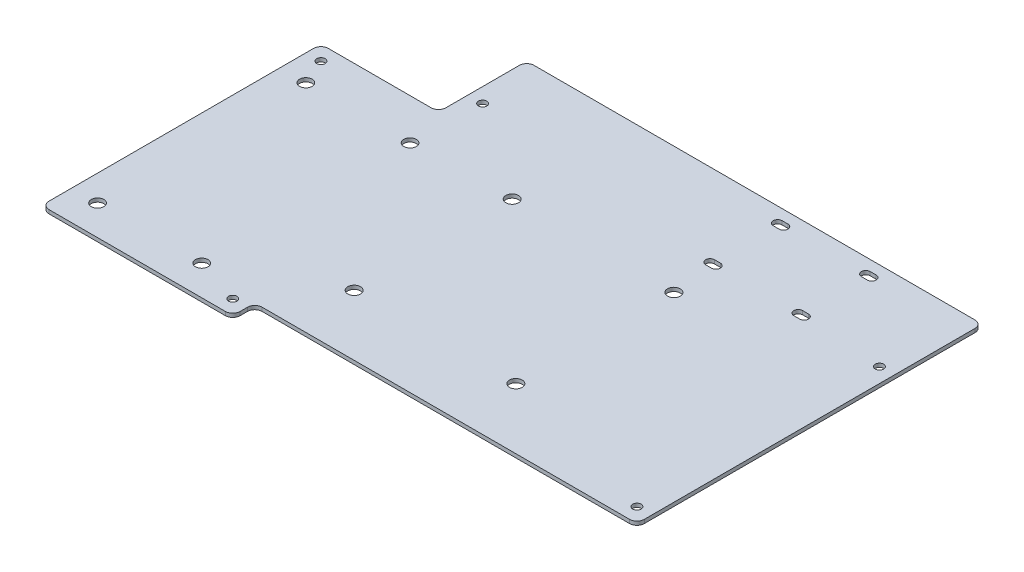
SolidWorks part; units mm, degrees
ref_plane "Front Plane" through (0, 0, 0) normal (0, 0, 1) x (1, 0, 0)
ref_plane "Top Plane" through (0, 0, 0) normal (0, 1, 0) x (1, 0, 0)
ref_plane "Right Plane" through (0, 0, 0) normal (1, 0, 0) x (0, 0, -1)
sketch "Sketch1" plane through (0, 0, 0) normal (0, 1, 0) x (1, 0, 0)
  line L1 (0, 0) -> (247.65, 0)
  line L2 (0, 0) -> (0, 120.65)
  line L3 (50.8, 158.75) -> (247.65, 158.75)
  line L4 (247.65, 0) -> (247.65, 158.75)
  line L15 (0, 120.65) -> (50.8, 120.65)
  line L16 (50.8, 158.75) -> (50.8, 120.65)
  line L21 (351.9786, 184.7613) -> (351.9786, -3.4747) construction
  dimension "D1" = 158.75
  dimension "D2" = 351.9786
  dimension "D4" = 247.65
  dimension "D6" = 38.1
  dimension "D7" = 50.8
extrude "Boss-Extrude1" add sketch "Sketch1" along normal blind 1.6002
sketch "Sketch3" plane through (0, 1.6002, 0) normal (0, 1, 0) x (1, 0, 0)
  line L0 (82.55, 0) -> (82.55, 9.525)
  line L1 (0, 0) -> (247.65, 0) construction
  line L2 (82.55, 9.525) -> (247.65, 9.525)
  line L8 (247.65, 0) -> (247.65, 158.75) construction
  line L10 (247.65, 0) -> (82.55, 0)
  line L11 (0, 0) -> (0, 120.65) construction
  line L12 (247.65, 9.525) -> (247.65, 0)
  dimension "D1" = 82.55
  dimension "D2" = 9.525
extrude "Cut-Extrude1" cut sketch "Sketch3" against normal through all
fillet "Fillet1" radius 3.175 8 edges at (82.55, 0.8001, 0) (0, 0.8001, -120.65) (50.8, 0.8001, -120.65) (50.8, 0.8001, -158.75) (247.65, 0.8001, -158.75) (247.65, 0.8001, -9.525) (82.55, 0.8001, -9.525) (0, 0.8001, 0)
sketch "Sketch4" plane through (0, 1.6002, 0) normal (0, 1, 0) x (1, 0, 0)
  line L0 (165.653, 152.32) -> (168.193, 152.32) construction
  line L1 (165.653, 154.225) -> (168.193, 154.225)
  line L2 (165.653, 150.415) -> (168.193, 150.415)
  line L5 (203.753, 152.32) -> (206.293, 152.32) construction
  line L6 (203.753, 154.225) -> (206.293, 154.225)
  line L7 (203.753, 150.415) -> (206.293, 150.415)
  line L8 (203.753, 123.11) -> (206.293, 123.11) construction
  line L9 (203.753, 125.015) -> (206.293, 125.015)
  line L10 (203.753, 121.205) -> (206.293, 121.205)
  line L11 (165.653, 123.11) -> (168.193, 123.11) construction
  line L12 (165.653, 125.015) -> (168.193, 125.015)
  line L13 (165.653, 121.205) -> (168.193, 121.205)
  line L15 (205.023, 123.11) -> (166.923, 123.11) construction
  line L16 (205.023, 123.11) -> (205.023, 152.32) construction
  line L17 (205.023, 152.32) -> (166.923, 152.32) construction
  line L18 (166.923, 123.11) -> (166.923, 152.32) construction
  line L19 (205.023, 123.11) -> (166.923, 152.32) construction
  line L20 (205.023, 152.32) -> (166.923, 123.11) construction
  line L21 (222.488, 125.015) -> (149.458, 125.015) construction
  line L22 (222.488, 125.015) -> (222.488, 150.415) construction
  line L23 (222.488, 150.415) -> (149.458, 150.415) construction
  line L24 (149.458, 125.015) -> (149.458, 150.415) construction
  line L25 (222.488, 125.015) -> (149.458, 150.415) construction
  line L26 (222.488, 150.415) -> (149.458, 125.015) construction
  arc A0 (165.653, 154.225) -> (165.653, 150.415) centre (165.653, 152.32) ccw
  arc A1 (168.193, 150.415) -> (168.193, 154.225) centre (168.193, 152.32) ccw
  arc A2 (203.753, 154.225) -> (203.753, 150.415) centre (203.753, 152.32) ccw
  arc A3 (206.293, 150.415) -> (206.293, 154.225) centre (206.293, 152.32) ccw
  arc A4 (203.753, 125.015) -> (203.753, 121.205) centre (203.753, 123.11) ccw
  arc A5 (206.293, 121.205) -> (206.293, 125.015) centre (206.293, 123.11) ccw
  arc A6 (165.653, 125.015) -> (165.653, 121.205) centre (165.653, 123.11) ccw
  arc A7 (168.193, 121.205) -> (168.193, 125.015) centre (168.193, 123.11) ccw
  point P2 (166.923, 152.32)
  point P12 (185.973, 137.715)
  point P13 (205.023, 152.32)
  point P20 (205.023, 123.11)
  point P27 (166.923, 123.11)
  point P36 (185.973, 137.715)
  dimension "D2" = 6.35
  dimension "D1" = 3.81
  dimension "D5" = 38.1
  dimension "D3" = 2
  dimension "D4" = 2
extrude "Fuse Ziptie Mounts" cut sketch "Sketch4" against normal through all
sketch "Sketch5" plane through (0, 1.6002, 0) normal (0, 1, 0) x (1, 0, 0)
  circle A0 centre (99.298, 103.9876) radius 2.75
  circle A1 centre (99.298, 35.7124) radius 2.75
  circle A2 centre (169.148, 103.9876) radius 2.75
  circle A3 centre (169.148, 35.7124) radius 2.75
  dimension "D1" = 5.5
extrude "Contactor Mounting Holes" cut sketch "Sketch5" against normal through all
sketch "Sketch6" plane through (0, 1.6002, 0) normal (0, 1, 0) x (1, 0, 0)
  line L0 (0, 3.175) -> (0, 117.475) construction
  line L1 (3.175, 120.65) -> (47.625, 120.65) construction
  line L2 (82.55, 6.35) -> (82.55, 3.175) construction
  line L3 (3.175, 0) -> (79.375, 0) construction
  line L4 (244.475, 9.525) -> (85.725, 9.525) construction
  line L5 (247.65, 12.7) -> (247.65, 155.575) construction
  line L6 (53.975, 158.75) -> (244.475, 158.75) construction
  line L7 (50.8, 155.575) -> (50.8, 123.825) construction
  circle A0 centre (6.35, 114.3) radius 1.8288
  circle A1 centre (76.2, 6.35) radius 1.8288
  circle A2 centre (241.3, 15.875) radius 1.8288
  circle A3 centre (241.3, 120.65) radius 1.8288
  circle A4 centre (57.15, 133.35) radius 1.8288
  point P10 (0, 0)
  point P23 (0, 0)
  point P26 (0, 0)
  dimension "D1" = 3.6576
  dimension "D2" = 6.35
  dimension "D3" = 6.35
  dimension "D4" = 6.35
  dimension "D5" = 6.35
  dimension "D6" = 6.35
  dimension "D7" = 6.35
  dimension "D8" = 38.1
  dimension "D9" = 6.35
  dimension "D10" = 25.4
extrude "Cut-Extrude2" cut sketch "Sketch6" against normal through all
sketch "Sketch7" plane through (0, 1.6002, 0) normal (0, 1, 0) x (1, 0, 0)
  circle A0 centre (11.198, 102.95) radius 2.7051
  circle A1 centre (56.198, 102.95) radius 2.7051
  circle A2 centre (11.198, 12.95) radius 2.7051
  circle A3 centre (56.198, 12.95) radius 2.7051
  dimension "D1" = 5.4102
extrude "Cut-Extrude3" cut sketch "Sketch7" against normal through all
